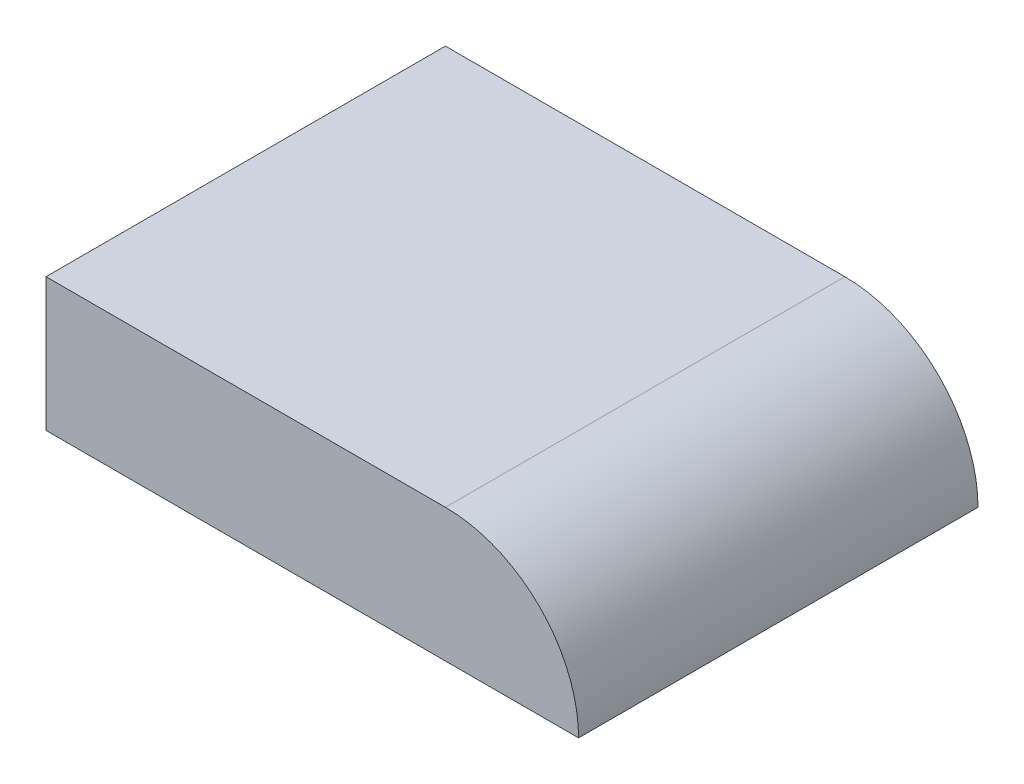
SolidWorks part; units mm, degrees
ref_plane "Front Plane" through (0, 0, 0) normal (0, 0, 1) x (1, 0, 0)
ref_plane "Top Plane" through (0, 0, 0) normal (0, 1, 0) x (1, 0, 0)
ref_plane "Right Plane" through (0, 0, 0) normal (1, 0, 0) x (0, 0, -1)
sketch "Sketch1" plane through (0, 0, 0) normal (0, 0, 1) x (1, 0, 0)
  line L0 (-40.2842, 44.9264) -> (-30.1242, 44.9264)
  line L1 (-40.2842, 44.9264) -> (-40.2842, 47.4664)
  line L2 (-40.2842, 47.4664) -> (-32.6642, 47.4664)
  arc A2 (-32.6642, 47.4664) -> (-30.1242, 44.9264) centre (-32.6642, 44.9264) cw
  dimension "D1" = 2.54
  dimension "D2" = 7.62
  dimension "D3" = 10.16
extrude "Boss-Extrude1" add sketch "Sketch1" along normal blind 7.62 contours L2 A2 L0 L1
ref_plane "Plane2" through (0, 44.9264, 0) normal (0, 1, 0) x (1, 0, 0)
